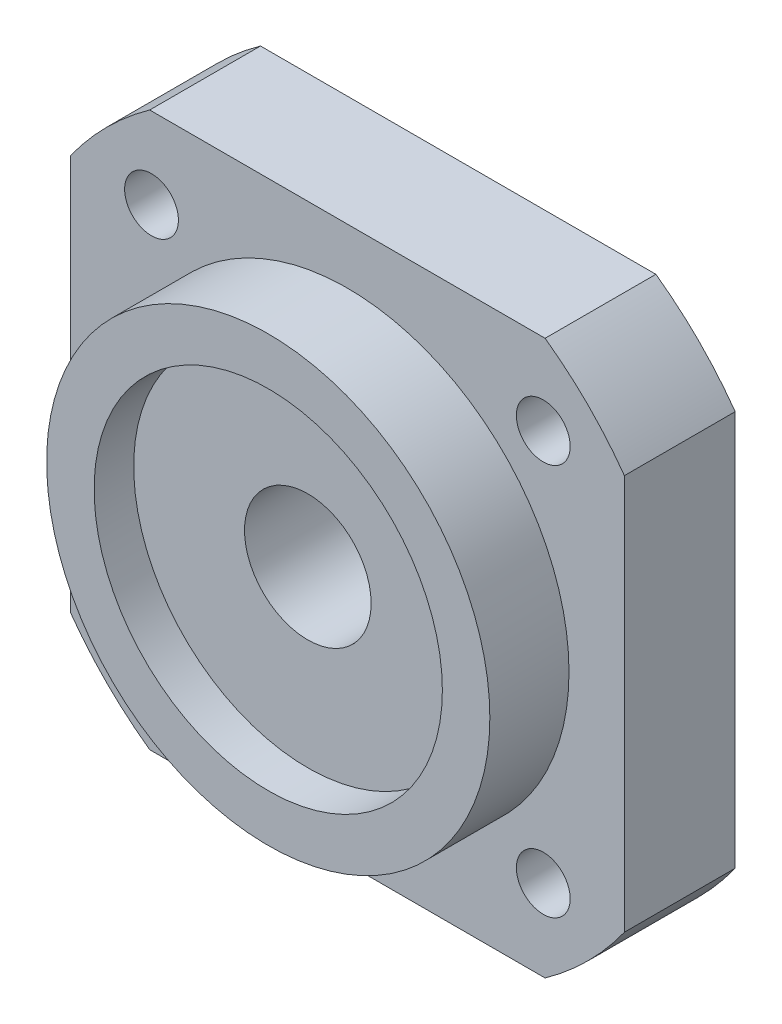
SolidWorks part; units mm, degrees
ref_plane "Plan de face" through (0, 0, 0) normal (0, 0, 1) x (1, 0, 0)
ref_plane "Plan de dessus" through (0, 0, 0) normal (0, 1, 0) x (1, 0, 0)
ref_plane "Plan de droite" through (0, 0, 0) normal (1, 0, 0) x (0, 0, -1)
ref_plane "Plan1" through (0, 0, 0) normal (0, 0, -1) x (-1, 0, 0)
sketch "Esquisse1" plane through (0, 0, 0) normal (0, 0, -1) x (-1, 0, 0)
  line L0 (-17.5, 12.49) -> (-17.5, -12.49)
  line L1 (-12.49, -17.5) -> (12.49, -17.5)
  line L2 (17.5, -12.49) -> (17.5, 12.49)
  line L3 (12.49, 17.5) -> (-12.49, 17.5)
  arc A0 (-17.5, -12.49) -> (-12.49, -17.5) centre (0, 0) ccw
  arc A1 (12.49, -17.5) -> (17.5, -12.49) centre (0, 0) ccw
  arc A2 (17.5, 12.49) -> (12.49, 17.5) centre (0, 0) ccw
  arc A3 (-12.49, 17.5) -> (-17.5, 12.49) centre (0, 0) ccw
extrude "Boss.-Extru.1" add sketch "Esquisse1" against normal blind 7
sketch "Esquisse2" plane through (0, 0, 0) normal (0, 1, 0) x (1, 0, 0)
  line L0 (14, -7) -> (0, -7)
  line L1 (0, -7) -> (0, -12)
  line L2 (0, -12) -> (14, -12)
  line L3 (14, -12) -> (14, -7)
  line L4 (0, -7) -> (0, -12) construction
revolve "Révolution1" add sketch "Esquisse2" angle 360 about L4
sketch "Esquisse3" plane through (0, 0, 0) normal (0, 1, 0) x (1, 0, 0)
  line L0 (11, 0) -> (0, 0)
  line L1 (0, 0) -> (0, -12)
  line L2 (0, -12) -> (11, -12)
  line L3 (11, -12) -> (11, -9.5)
  line L4 (11, -9.5) -> (4, -9.5)
  line L5 (4, -9.5) -> (4, -2.5)
  line L6 (4, -2.5) -> (11, -2.5)
  line L7 (11, -2.5) -> (11, 0)
  line L8 (0, 0) -> (0, -12) construction
revolve "Enlèvement de matière-Révolution1" cut sketch "Esquisse3" angle 360 about L8
hole_wizard "Chambrage pour vis à tête hexagonale M31" positions "Esquisse5" profile "Esquisse4" counterbore size "M3" standard "Ansi Metric"
sketch "Esquisse5" plane through (0, 0, 0) normal (0, 0, -1) x (-1, 0, 0)
  point P0 (12.3744, 12.3744)
  point P1 (-12.3744, 12.3744)
  point P2 (-12.3744, -12.3744)
  point P3 (12.3744, -12.3744)
sketch "Esquisse4" plane through (-12.3744, 12.3744, 0) normal (1, 0, 0) x (0, 1, 0)
  line L0 (0, 0) -> (0, 12)
  line L1 (0, 12) -> (1.7, 12)
  line L3 (1.7, 12) -> (1.7, 3.3)
  line L4 (1.7, 3.3) -> (3, 3.3)
  line L5 (3, 3.3) -> (3, 0)
  line L7 (3, 0) -> (0, 0)
  line L11 (0, -6.35) -> (0, 107.95) construction
  dimension "Diamètre du perçage jusqu'au prochain" = 3.4
  dimension "Profondeur du perçage jusqu'au prochain" = 12
  dimension "Diamètre du chambrage" = 6
  dimension "Profondeur du chambrage" = 3.3
